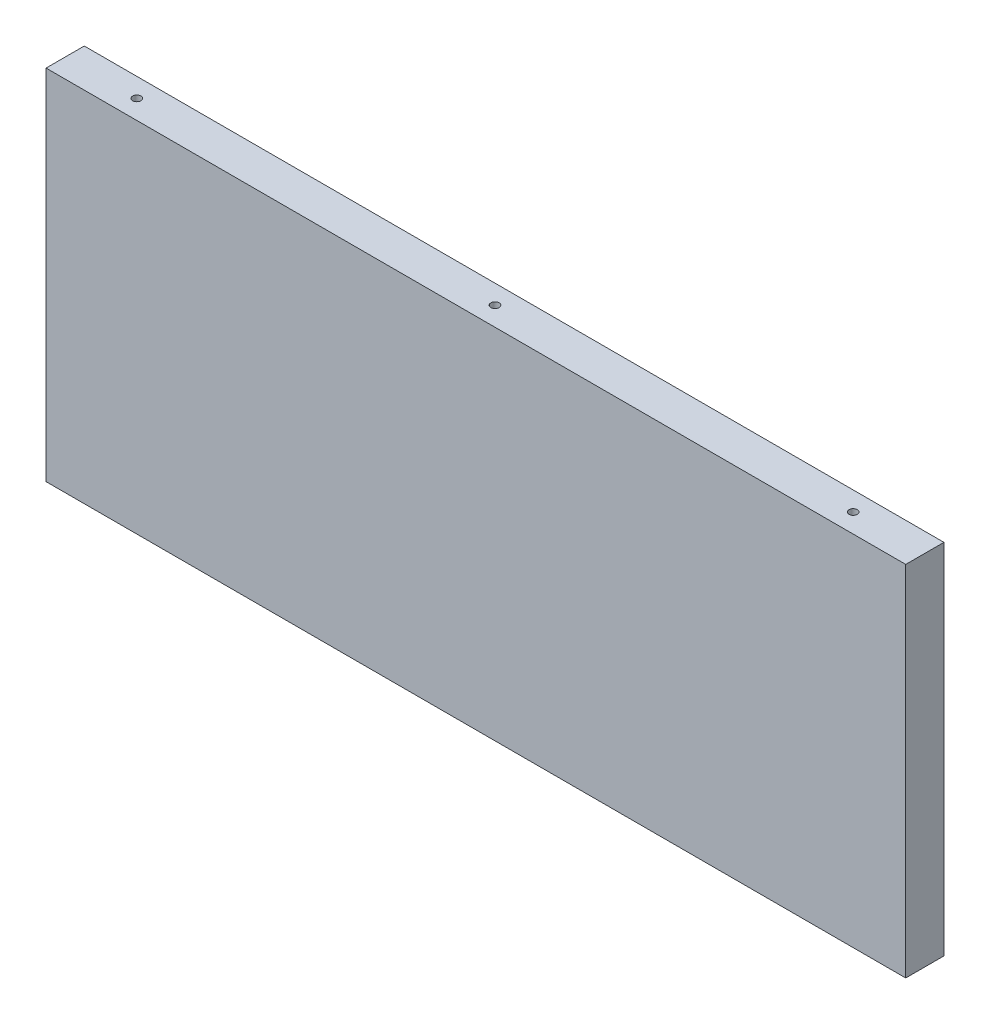
SolidWorks part; units mm, degrees
ref_plane "Front Plane" through (0, 0, 0) normal (0, 0, 1) x (1, 0, 0)
ref_plane "Top Plane" through (0, 0, 0) normal (0, 1, 0) x (1, 0, 0)
ref_plane "Right Plane" through (0, 0, 0) normal (1, 0, 0) x (0, 0, -1)
other "Bounding Box"
ref_plane "Default Plane" through (-180, -75, -8) normal (0, 1, 0) x (1, 0, 0)
sketch "Sketch1" plane through (0, 0, 0) normal (0, 0, 1) x (1, 0, 0)
  line L1 (-180, -75) -> (180, -75)
  line L2 (-180, -75) -> (-180, 75)
  line L3 (-180, 75) -> (180, 75)
  line L4 (180, -75) -> (180, 75)
  line L5 (-180, -75) -> (180, 75) construction
  line L6 (-180, 75) -> (180, -75) construction
  point P0 (0, 0)
  dimension "D1" = 150
  dimension "D2" = 360
extrude "Boss-Extrude1" add sketch "Sketch1" along normal mid plane 16
hole_wizard "#8-36 Tapped Hole1" positions "Sketch4" profile "Sketch3" tap size "#8-36" standard "ANSI Inch"
sketch "Sketch4" plane through (0, -75, 0) normal (0, -1, 0) x (-1, 0, 0)
  line L0 (180, -8) -> (180, 8) construction
  line L1 (111.5, 0) -> (142.5, 0) construction
  line L3 (180, 8) -> (-180, 8) construction
  line L4 (180, -8) -> (-180, -8) construction
  point P0 (142.5, 0)
  point P2 (111.5, 0)
  dimension "D1" = 37.5
  dimension "D2" = 31
sketch "Sketch3" plane through (-142.5, -75, 0) normal (1, 0, 0) x (0, 0, -1)
  line L0 (0, 0) -> (0, 26.0378)
  line L1 (0, 26.0378) -> (1.7272, 25)
  line L2 (1.7272, 25) -> (1.7272, 0)
  line L5 (1.7272, 0) -> (0, 0)
  line L10 (0, 26.0378) -> (-1.7272, 25) construction
  line L11 (0, -6.35) -> (0, 107.95) construction
  dimension "Tap Drill Dia." = 3.4544
  dimension "Tap Drill Depth" = 25
  dimension "Drill Angle" = 118
cosmetic thread "Hole Thread1" parameters "D1"=20, "D2"=4.1656
cosmetic thread "Hole Thread2" parameters "D1"=20, "D2"=4.1656
hole_wizard "M8 Clearance Hole1" positions "Sketch7" profile "Sketch6" hole size "M8" standard "ANSI Metric"
sketch "Sketch7" plane through (0, -75, 0) normal (0, -1, 0) x (-1, 0, 0)
  line L0 (111.5, 0) -> (142.5, 0) construction
  point P0 (127, 0)
  point P12 (127, 0)
sketch "Sketch6" plane through (-127, -75, 0) normal (1, 0, 0) x (0, 0, -1)
  line L0 (0, 0) -> (0, 48.0043)
  line L1 (0, 48.0043) -> (5, 45)
  line L2 (5, 45) -> (5, 0)
  line L5 (5, 0) -> (0, 0)
  line L10 (0, 48.0043) -> (-5, 45) construction
  line L11 (0, -6.35) -> (0, 107.95) construction
  dimension "Hole Dia." = 10
  dimension "Hole Depth" = 45
  dimension "Drill Angle" = 118
mirror "Mirror1" about plane through (0, 0, 0) normal (1, 0, 0) of "M8 Clearance Hole1", "#8-36 Tapped Hole1"
cosmetic thread "Hole Thread3" parameters "D1"=20, "D2"=4.1656
cosmetic thread "Hole Thread4" parameters "D1"=20, "D2"=4.1656
hole_wizard "#8-36 Tapped Hole2" positions "Sketch8" profile "Sketch9" tap size "#8-36" standard "ANSI Inch"
sketch "Sketch8" plane through (597.7049, 75, -222) normal (0, 1, 0) x (1, 0, 0)
  line L1 (-447.7049, -222) -> (-747.7049, -222) construction
  line L6 (-597.7049, -222) -> (-597.7049, -129.5989) construction
  point P0 (-447.7049, -222)
  point P1 (-597.7049, -222)
  point P2 (-747.7049, -222)
sketch "Sketch9" plane through (150, 75, 0) normal (1, 0, 0) x (0, 0, 1)
  line L0 (0, 0) -> (0, 26.0378)
  line L1 (0, 26.0378) -> (1.7272, 25)
  line L2 (1.7272, 25) -> (1.7272, 0)
  line L5 (1.7272, 0) -> (0, 0)
  line L10 (0, 26.0378) -> (-1.7272, 25) construction
  line L11 (0, -6.35) -> (0, 107.95) construction
  dimension "Tap Drill Dia." = 3.4544
  dimension "Tap Drill Depth" = 25
  dimension "Drill Angle" = 118
cosmetic thread "Hole Thread23"
cosmetic thread "Hole Thread25"
cosmetic thread "Hole Thread26"
